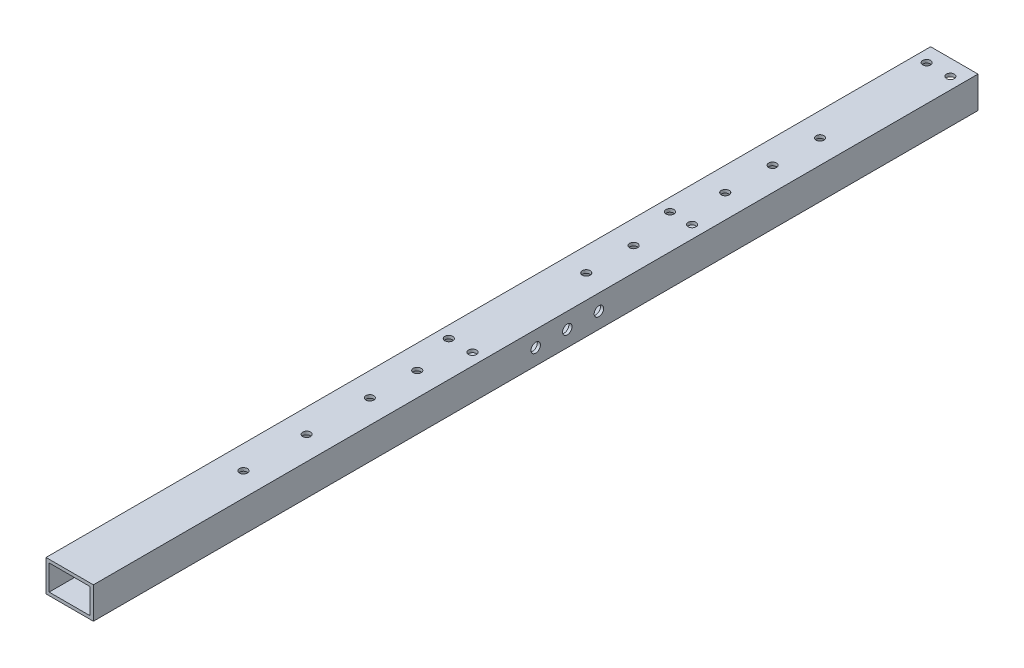
SolidWorks part; units mm, degrees
material "6063-T5"
ref_plane "前视基准面" through (0, 0, 0) normal (0, 0, 1) x (1, 0, 0)
ref_plane "上视基准面" through (0, 0, 0) normal (0, 1, 0) x (1, 0, 0)
ref_plane "右视基准面" through (0, 0, 0) normal (1, 0, 0) x (0, 0, -1)
sketch "草图1" plane through (0, 0, 0) normal (0, 0, 1) x (1, 0, 0)
  line L1 (-15, 10) -> (15, 10)
  line L2 (-15, 10) -> (-15, -10)
  line L3 (-15, -10) -> (15, -10)
  line L4 (15, 10) -> (15, -10)
  line L5 (-15, 10) -> (15, -10) construction
  line L6 (-15, -10) -> (15, 10) construction
  line L7 (-13, 8) -> (13, 8)
  line L8 (-13, 8) -> (-13, -8)
  line L9 (-13, -8) -> (13, -8)
  line L10 (13, 8) -> (13, -8)
  line L11 (-13, 8) -> (13, -8) construction
  line L12 (-13, -8) -> (13, 8) construction
  point P0 (0, 0)
  point P5 (0, 0)
  point P11 (13, 0)
  dimension "D1" = 30
  dimension "D2" = 20
  dimension "D3" = 2
  dimension "D4" = 2
extrude "凸台-拉伸1" add sketch "草图1" along normal blind 560
sketch "草图3" plane through (0, 10, 0) normal (0, 1, 0) x (1, 0, 0)
  circle A0 centre (-7.5, -10) radius 2.5
  circle A1 centre (7.5, -10) radius 2.5
  dimension "D1" = 5
  dimension "D2" = 5
extrude "切除-拉伸2" cut sketch "草图3" against normal through all
sketch "草图4" plane through (0, 10, 0) normal (0, 1, 0) x (1, 0, 0)
  line L0 (0, -254.3928) -> (0, -348.8334) construction
  circle A0 centre (-7.5, -312.5) radius 2.5
  circle A1 centre (7.5, -312.5) radius 2.5
  dimension "D1" = 5
  dimension "D3" = 15
  dimension "D2" = 312.5
extrude "切除-拉伸3" cut sketch "草图4" against normal through all
sketch "草图7" plane through (-15, 0, 0) normal (-1, 0, 0) x (0, 0, 1)
  line L0 (0, 0) -> (331.8923, 0) construction
  circle A0 centre (260, 0) radius 3
  circle A1 centre (280, 0) radius 3
  circle A2 centre (240, 0) radius 3
  dimension "D1" = 6
  dimension "D2" = 6
  dimension "D3" = 6
  dimension "D4" = 20
  dimension "D5" = 20
  dimension "D6" = 260
extrude "切除-拉伸5" cut sketch "草图7" against normal blind 30
sketch "草图8" plane through (0, 10, 0) normal (0, 1, 0) x (1, 0, 0)
  line L0 (0, 87.6502) -> (0, -691.0579) construction
  line L2 (15, -560) -> (-15, -560) construction
  circle A2 centre (0, -370) radius 2.5
  circle A3 centre (0, -450) radius 2.5
  circle A6 centre (0, -410) radius 2.5
  circle A7 centre (0, -340) radius 2.5
  dimension "D9" = 5
  dimension "D10" = 5
  dimension "D11" = 5
  dimension "D12" = 40
  dimension "D13" = 40
  dimension "D14" = 110
  dimension "D15" = 5
  dimension "D16" = 30
extrude "切除-拉伸6" cut sketch "草图8" against normal blind 30
sketch "草图10" plane through (0, 10, 0) normal (0, 1, 0) x (1, 0, 0)
  line L0 (0, 60.3559) -> (0, -598.4328) construction
  line L1 (-15, -173) -> (15, -173) construction
  line L2 (-15, -560) -> (-15, 0) construction
  line L3 (15, -560) -> (15, 0) construction
  line L4 (15, 0) -> (-15, 0) construction
  circle A0 centre (-7, -173) radius 2.5
  circle A1 centre (7, -173) radius 2.5
  dimension "D2" = 5
  dimension "D3" = 5
  dimension "D4" = 7
  dimension "D5" = 7
  dimension "D1" = 173
extrude "切除-拉伸7" cut sketch "草图10" against normal blind 30
sketch "草图11" plane through (0, 10, 0) normal (0, 1, 0) x (1, 0, 0)
  line L0 (0, 52.9185) -> (0, -291.7867) construction
  line L1 (15, 0) -> (-15, 0) construction
  circle A0 centre (0, -85) radius 2.5
  circle A1 centre (0, -115) radius 2.5
  circle A2 centre (0, -203) radius 2.5
  circle A3 centre (0, -233) radius 2.5
  circle A4 centre (7, -173) radius 2.5 construction
  circle A6 centre (0, -145) radius 2.5
  dimension "D2" = 30
  dimension "D3" = 30
  dimension "D4" = 30
  dimension "D5" = 5
  dimension "D6" = 5
  dimension "D7" = 5
  dimension "D8" = 5
  dimension "D9" = 5
  dimension "D10" = 30
  dimension "D1" = 85
extrude "切除-拉伸8" cut sketch "草图11" against normal blind 30
